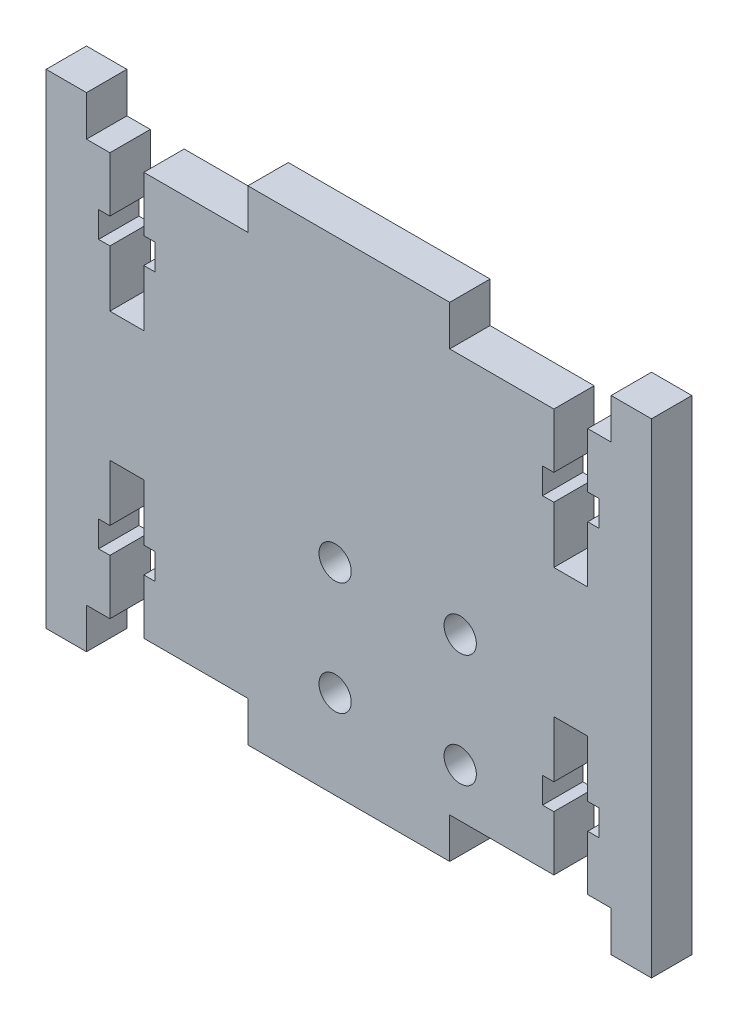
SolidWorks part; units mm, degrees
ref_plane "Front Plane" through (0, 0, 0) normal (0, 0, 1) x (1, 0, 0)
ref_plane "Top Plane" through (0, 0, 0) normal (0, 1, 0) x (1, 0, 0)
ref_plane "Right Plane" through (0, 0, 0) normal (1, 0, 0) x (0, 0, -1)
sketch "Sketch1" plane through (0, 0, 0) normal (0, 0, 1) x (1, 0, 0)
  line L0 (32.5, 55) -> (32.5, 28.1875) construction
  line L1 (0, 50) -> (65, 50)
  line L2 (0, 50) -> (0, 0)
  line L3 (0, 0) -> (65, 0)
  line L4 (65, 50) -> (65, 0)
  line L5 (20, 50) -> (45, 50)
  line L6 (20, 50) -> (20, 55)
  line L7 (20, 55) -> (45, 55)
  line L8 (45, 50) -> (45, 55)
  line L9 (2.9, 50) -> (7.1, 50)
  line L10 (2.9, 50) -> (2.9, 33)
  line L11 (2.9, 33) -> (7.1, 33)
  line L12 (7.1, 50) -> (7.1, 33)
  line L13 (1.5, 43.2) -> (8.5, 43.2)
  line L14 (1.5, 43.2) -> (1.5, 40)
  line L15 (1.5, 40) -> (8.5, 40)
  line L16 (8.5, 43.2) -> (8.5, 40)
  line L17 (63.5, 40) -> (56.5, 40)
  line L18 (56.5, 43.2) -> (56.5, 40)
  line L19 (63.5, 43.2) -> (56.5, 43.2)
  line L20 (63.5, 43.2) -> (63.5, 40)
  line L21 (62.1, 33) -> (57.9, 33)
  line L22 (57.9, 50) -> (57.9, 33)
  line L23 (62.1, 50) -> (57.9, 50)
  line L24 (62.1, 50) -> (62.1, 33)
  line L25 (0, 25) -> (24.3939, 25) construction
  line L26 (20, -5) -> (45, -5)
  line L27 (45, 0) -> (45, -5)
  line L28 (20, 0) -> (45, 0)
  line L29 (20, 0) -> (20, -5)
  line L30 (62.1, 0) -> (62.1, 17)
  line L31 (62.1, 0) -> (57.9, 0)
  line L32 (57.9, 0) -> (57.9, 17)
  line L33 (62.1, 17) -> (57.9, 17)
  line L34 (63.5, 6.8) -> (63.5, 10)
  line L35 (63.5, 6.8) -> (56.5, 6.8)
  line L36 (56.5, 6.8) -> (56.5, 10)
  line L37 (63.5, 10) -> (56.5, 10)
  line L38 (1.5, 10) -> (8.5, 10)
  line L39 (8.5, 6.8) -> (8.5, 10)
  line L40 (1.5, 6.8) -> (8.5, 6.8)
  line L41 (1.5, 6.8) -> (1.5, 10)
  line L42 (2.9, 17) -> (7.1, 17)
  line L43 (7.1, 0) -> (7.1, 17)
  line L44 (2.9, 0) -> (7.1, 0)
  line L45 (2.9, 0) -> (2.9, 17)
  line L46 (65, -5) -> (70, -5)
  line L47 (0, 55) -> (-5, 55)
  line L48 (0, 55) -> (0, -5)
  line L49 (0, -5) -> (-5, -5)
  line L50 (-5, 55) -> (-5, -5)
  line L51 (70, 55) -> (70, -5)
  line L52 (65, 55) -> (70, 55)
  line L53 (65, 55) -> (65, -5)
  point P17 (5, 43.2)
  point P18 (5, 33)
  dimension "D1" = 50
  dimension "D2" = 5
  dimension "D3" = 25
  dimension "D4" = 20
  dimension "D5" = 20
  dimension "D6" = 7
  dimension "D7" = 3.2
  dimension "D8" = 6.8
  dimension "D9" = 17
  dimension "D10" = 4.2
  dimension "D11" = 5
  dimension "D12" = 5
extrude "Boss-Extrude1" add sketch "Sketch1" along normal blind 5 contours L3 L45 L40 L41 L38 L42 L43 L39 L32 L35 L36 L37 L33 L30 L34 L4 L1 L24 L19 L20 L17 L21 L22 L18 L12 L13 L16 L15 L11 L10 | L1 L8 L7 L6 | L3 L29 L26 L27 | L48 L47 L50 L49 | L46 L51 L52 L53
sketch "Sketch2" plane through (0, 0, 0) normal (0, 0, -1) x (-1, 0, 0)
  circle A0 centre (-46.3, 20) radius 2 construction
  circle A1 centre (-46.3, 6) radius 2 construction
  circle A2 centre (-30.8, 6) radius 2 construction
  circle A3 centre (-30.8, 20) radius 2 construction
  circle A4 centre (-46.3, 20) radius 2
  circle A5 centre (-46.3, 6) radius 2
  circle A6 centre (-30.8, 6) radius 2
  circle A7 centre (-30.8, 20) radius 2
extrude "Cut-Extrude2" cut sketch "Sketch2" against normal blind 5
move or copy body "Body-Move/Copy1" [suppressed] bodies to move or copy 101
